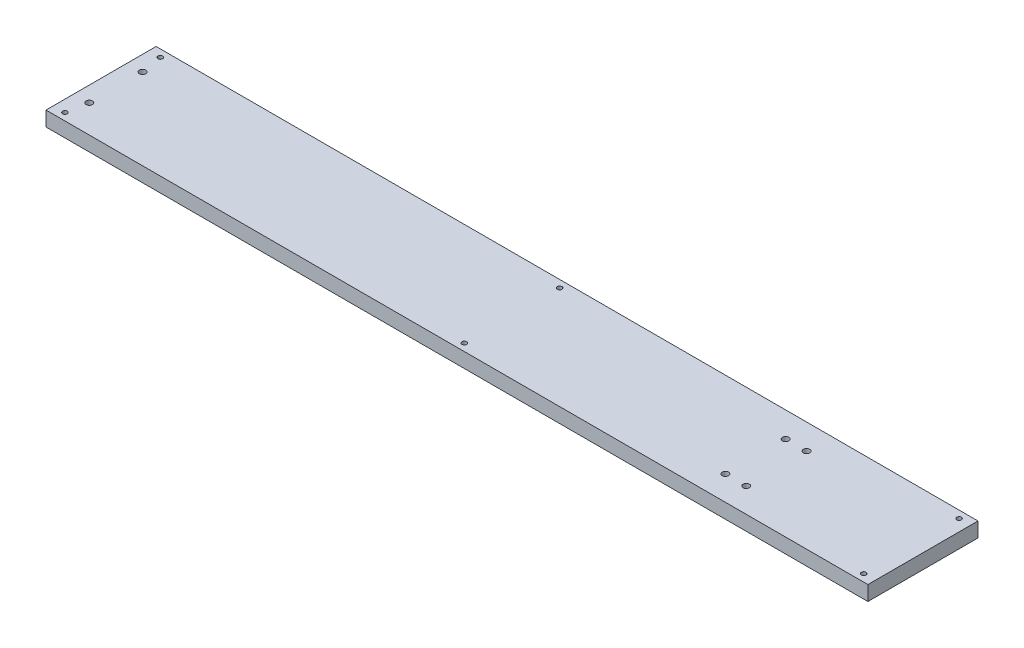
SolidWorks part; units mm, degrees
material "PE High Density Film"
ref_plane "Front Plane" through (0, 0, 0) normal (0, 0, 1) x (1, 0, 0)
ref_plane "Top Plane" through (0, 0, 0) normal (0, 1, 0) x (1, 0, 0)
ref_plane "Right Plane" through (0, 0, 0) normal (1, 0, 0) x (0, 0, -1)
sketch "Sketch1" plane through (0, 0, 0) normal (0, 1, 0) x (1, 0, 0)
  line L1 (0, 0) -> (709, 0)
  line L2 (0, 0) -> (0, 95)
  line L3 (0, 95) -> (709, 95)
  line L4 (709, 0) -> (709, 95)
  dimension "D1" = 95
  dimension "D2" = 709
extrude "Boss-Extrude1" add sketch "Sketch1" along normal blind 12.7
sketch "Sketch2" plane through (0, 0, 0) normal (0, -1, 0) x (1, 0, 0)
  line L0 (0, -6.35) -> (709, -6.35) construction
  line L1 (0, -95) -> (0, 0) construction
  line L2 (709, 0) -> (709, -95) construction
  line L3 (709, -88.65) -> (0, -88.65) construction
  line L5 (0, 0) -> (709, 0) construction
  line L6 (709, -95) -> (0, -95) construction
  circle A0 centre (10, -88.65) radius 2.0195
  circle A1 centre (354.5, -88.65) radius 2.0195
  circle A2 centre (699, -88.65) radius 2.0195
  circle A3 centre (699, -6.35) radius 2.0195
  circle A4 centre (354.5, -6.35) radius 2.0195
  circle A5 centre (10, -6.35) radius 2.0195
  dimension "D1" = 4.039
  dimension "D2" = 4.039
  dimension "D3" = 4.039
  dimension "D4" = 4.039
  dimension "D5" = 4.039
  dimension "D6" = 4.039
  dimension "D7" = 344.5
  dimension "D8" = 344.5
  dimension "D9" = 344.5
  dimension "D10" = 344.5
  dimension "D12" = 6.35
  dimension "D13" = 6.35
extrude "Cut-Extrude1" cut sketch "Sketch2" against normal through all
sketch "Sketch3" plane through (0, 0, 0) normal (0, -1, 0) x (1, 0, 0)
  line L2 (548.7315, 0) -> (548.7315, -18.4658) construction
  line L3 (0, 0) -> (709, 0) construction
  circle A0 centre (582.857, -21.2158) radius 2.75
  circle A1 centre (564.857, -21.2158) radius 2.75
  circle A2 centre (564.857, -73.2158) radius 2.75
  circle A3 centre (582.857, -73.2158) radius 2.75
  dimension "D3" = 5.5
  dimension "D1" = 18.4658
  dimension "D4" = 2
  dimension "D5" = 2
extrude "Cut-Extrude2" cut sketch "Sketch3" against normal through all
sketch "Sketch4" plane through (0, 0, 0) normal (0, -1, 0) x (1, 0, 0)
  line L0 (13.208, -95.1739) -> (13.208, 0) construction
  line L1 (0, 0) -> (709, 0) construction
  line L2 (23.5862, -24.13) -> (0, -24.13) construction
  line L3 (0, -95) -> (0, 0) construction
  line L4 (23.5862, -70.108) -> (0, -70.108) construction
  line L5 (709, -95) -> (0, -95) construction
  circle A0 centre (13.208, -24.13) radius 2.75
  circle A1 centre (13.208, -70.108) radius 2.75
  dimension "D4" = 5.5
  dimension "D5" = 5.5
  dimension "D1" = 24.892
  dimension "D2" = 24.13
  dimension "D3" = 13.208
extrude "Cut-Extrude3" cut sketch "Sketch4" against normal through all
